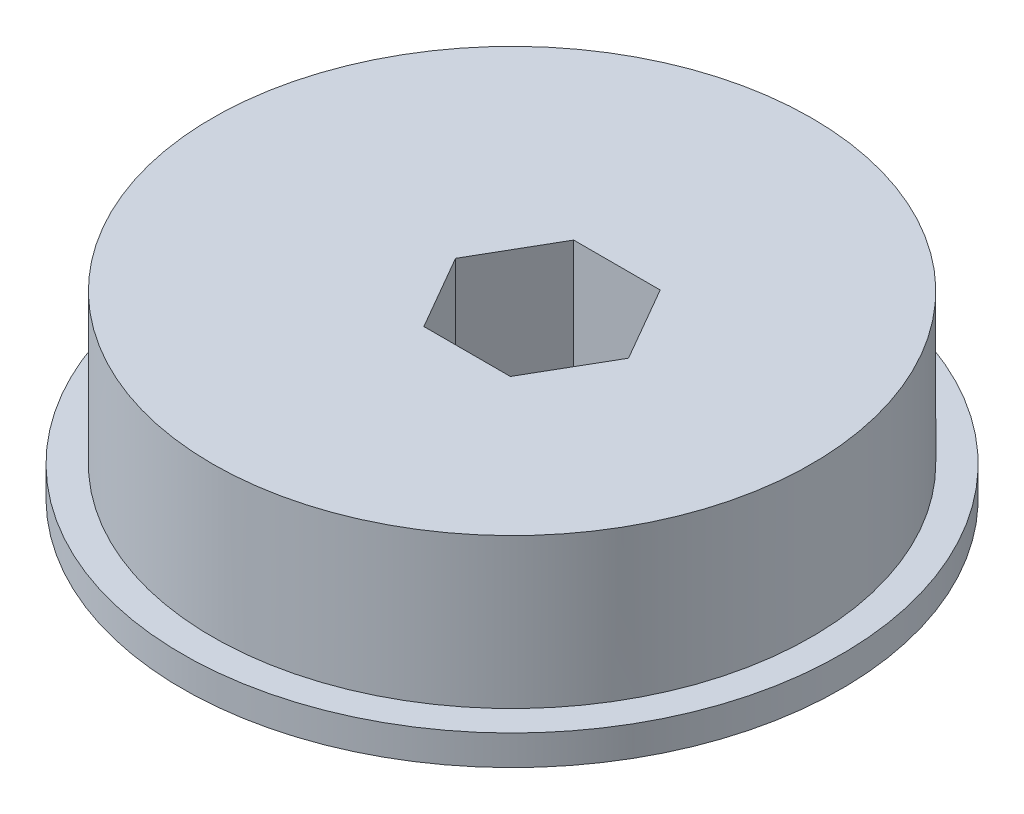
SolidWorks part; units mm, degrees
ref_plane "Front Plane" through (0, 0, 0) normal (0, 0, 1) x (1, 0, 0)
ref_plane "Top Plane" through (0, 0, 0) normal (0, 1, 0) x (1, 0, 0)
ref_plane "Right Plane" through (0, 0, 0) normal (1, 0, 0) x (0, 0, -1)
sketch "Sketch1" plane through (0, 0, 0) normal (0, 1, 0) x (1, 0, 0)
  line L0 (0, 0) -> (-1, 0) construction
  circle A1 centre (-1, 0) radius 10
  point P12 (0, 0)
  dimension "D3" = 20
  dimension "D2" = 1
extrude "Boss-Extrude1" add sketch "Sketch1" along normal blind 6
sketch "Sketch2" plane through (0, 0, 0) normal (0, -1, 0) x (1, 0, 0)
  line L0 (-12.8187, 0) -> (7.6603, 0) construction
  circle A0 centre (-1, 0) radius 11
  dimension "D2" = 22
  dimension "D1" = 1
extrude "Boss-Extrude2" add sketch "Sketch2" against normal blind 1
sketch "Sketch4" plane through (0, 6, 0) normal (0, 1, 0) x (1, 0, 0)
  line L0 (0, 8.8969) -> (0, -8.7328) construction
  line L2 (2.8868, 0) -> (1.4434, 2.5)
  line L3 (1.4434, 2.5) -> (-1.4434, 2.5)
  line L4 (-1.4434, 2.5) -> (-2.8868, 0)
  line L5 (-2.8868, 0) -> (-1.4434, -2.5)
  line L6 (-1.4434, -2.5) -> (1.4434, -2.5)
  line L7 (1.4434, -2.5) -> (2.8868, 0)
  circle A0 centre (0, 0) radius 5.5 construction
  circle A3 centre (0, 0) radius 2.5 construction
  dimension "D1" = 11
  dimension "D2" = 5
extrude "Cut-Extrude1" cut sketch "Sketch4" against normal through all
